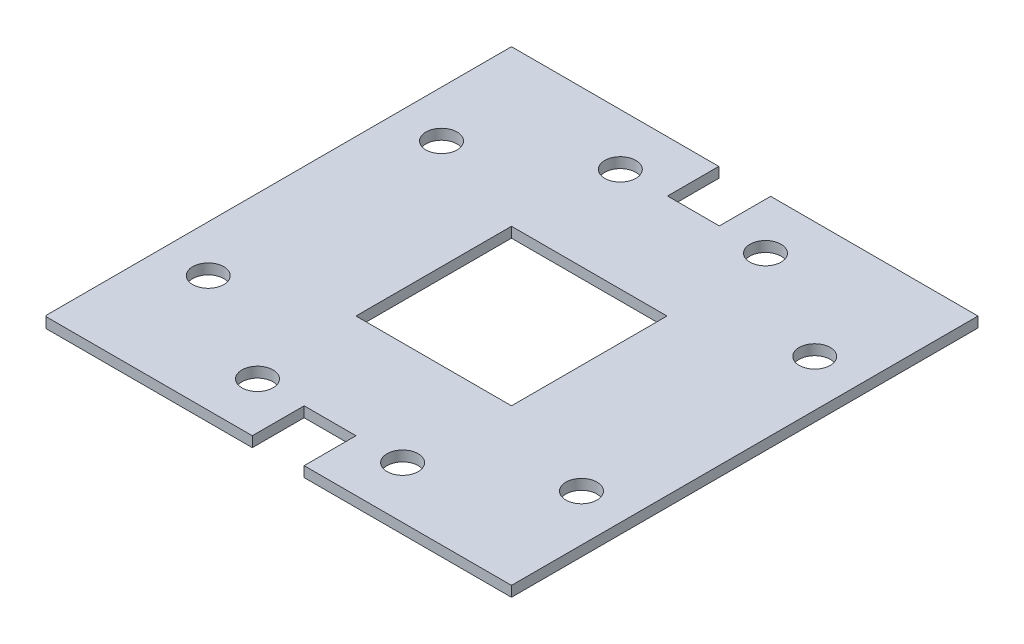
SolidWorks part; units mm, degrees
ref_plane "Alzado" through (0, 0, 0) normal (0, 0, 1) x (1, 0, 0)
ref_plane "Planta" through (0, 0, 0) normal (0, 1, 0) x (1, 0, 0)
ref_plane "Vista lateral" through (0, 0, 0) normal (1, 0, 0) x (0, 0, -1)
sketch "Croquis1" plane through (0, 0, 0) normal (0, 1, 0) x (1, 0, 0)
  line L0 (0, 0) -> (15, 15) construction
  line L1 (0, 0) -> (15, 0)
  line L2 (0, 0) -> (0, 15)
  line L3 (0, 15) -> (15, 15)
  line L4 (15, 0) -> (15, 15)
  line L5 (-15, -15) -> (30, -15)
  line L6 (-15, -15) -> (-15, 30)
  line L7 (-15, 30) -> (30, 30)
  line L8 (30, -15) -> (30, 30)
  line L9 (-15, 30) -> (30, -15) construction
  line L10 (-17.4749, 32.4749) -> (-15, 30) construction
  line L11 (25.5, 7.5) -> (30, 7.5) construction
  line L12 (7.5, 7.5) -> (7.5, -17.4738) construction
  line L13 (7.5, 7.5) -> (0, 7.5) construction
  line L14 (7.5, 22.5) -> (7.5, 30) construction
  line L15 (-7.5, 22.5) -> (22.5, 22.5) construction
  line L16 (-7.5, 22.5) -> (-7.5, -7.5) construction
  line L17 (-7.5, -7.5) -> (22.5, -7.5) construction
  line L18 (22.5, 22.5) -> (22.5, -7.5) construction
  line L19 (-7.5, 22.5) -> (22.5, -7.5) construction
  line L20 (-7.5, -7.5) -> (22.5, 22.5) construction
  line L21 (25.5, -3.75) -> (25.5, 7.5) construction
  line L22 (25.5, 7.5) -> (25.5, 18.75) construction
  line L23 (0.5, 25) -> (7.5, 25) construction
  line L24 (7.5, 25) -> (14.5, 25) construction
  circle A4 centre (-10.5, 18.75) radius 1.5
  circle A5 centre (-10.5, -3.75) radius 1.5
  circle A9 centre (0.5, 25) radius 1.5
  circle A10 centre (14.5, 25) radius 1.5
  arc A12 (-15, -14.8985) -> (-14.8985, -15) centre (-12.4749, -12.4749) ccw
  circle A13 centre (14.5, -10) radius 1.5
  circle A17 centre (0.5, -10) radius 1.5
  circle A23 centre (25.5, 18.75) radius 1.5
  circle A24 centre (25.5, -3.75) radius 1.5
  point P9 (7.5, 7.5)
  point P10 (7.5, 7.5)
  dimension "D3" = 18
  dimension "D4" = 3
  dimension "D9" = 3
  dimension "D1" = 15
  dimension "D2" = 45
  dimension "D5" = 3.5
  dimension "D6" = 7
  dimension "D8" = 30
  dimension "D10" = 11.25
  dimension "D7" = 17.5
extrude "Saliente-Extruir1" add sketch "Croquis1" along normal blind 1
sketch "Croquis3" plane through (0, 1, 0) normal (0, 1, 0) x (1, 0, 0)
  line L0 (-15, 30) -> (30, 30) construction
  line L1 (5, 30) -> (10, 30)
  line L2 (5, 30) -> (5, 25.0508)
  line L3 (5, 25.0508) -> (10, 25.0508)
  line L4 (10, 30) -> (10, 25.0508)
  line L5 (-14.8985, -15) -> (30, -15) construction
  line L6 (5, -15) -> (10, -15)
  line L7 (5, -15) -> (5, -10)
  line L8 (5, -10) -> (10, -10)
  line L9 (10, -15) -> (10, -10)
  line L10 (-15, 7.5508) -> (30, 7.5) construction
  line L11 (-15, -14.8985) -> (-15, 30) construction
  line L12 (30, -15) -> (30, 30) construction
  line L13 (7.5, 25.0508) -> (7.5, 7.5254) construction
  line L14 (7.5, 7.5254) -> (7.5, -10) construction
  dimension "D1" = 5
extrude "Cortar-Extruir2" cut sketch "Croquis3" against normal blind 10
